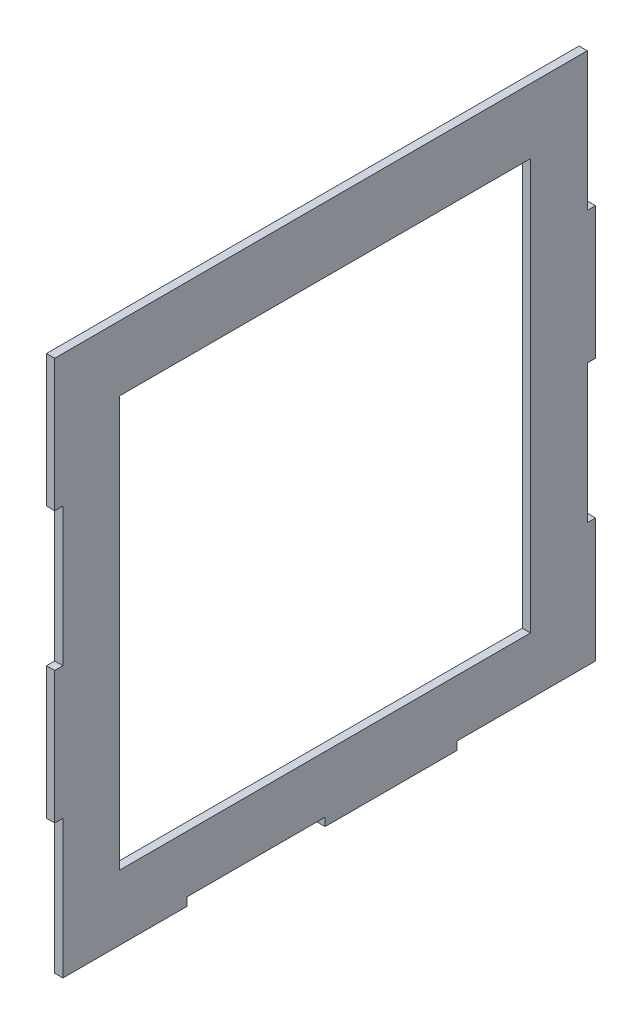
SolidWorks part; units mm, degrees
ref_plane "Front Plane" through (0, 0, 0) normal (0, 0, 1) x (1, 0, 0)
ref_plane "Top Plane" through (0, 0, 0) normal (0, 1, 0) x (1, 0, 0)
ref_plane "Right Plane" through (0, 0, 0) normal (1, 0, 0) x (0, 0, -1)
sketch "Sketch2" plane through (0, 0, 0) normal (1, 0, 0) x (0, 0, -1)
  line L1 (-197.5, -197.5) -> (197.5, -197.5)
  line L2 (-197.5, -197.5) -> (-197.5, 197.5)
  line L3 (-197.5, 197.5) -> (197.5, 197.5)
  line L4 (197.5, -197.5) -> (197.5, 197.5)
  line L5 (-197.5, -197.5) -> (197.5, 197.5) construction
  line L6 (-197.5, 197.5) -> (197.5, -197.5) construction
  line L7 (-150, -150) -> (150, -150)
  line L8 (-150, -150) -> (-150, 150)
  line L9 (-150, 150) -> (150, 150)
  line L10 (150, -150) -> (150, 150)
  line L11 (-150, -150) -> (150, 150) construction
  line L12 (-150, 150) -> (150, -150) construction
  line L13 (197.5, -197.5) -> (96.5, -197.5)
  line L14 (197.5, -197.5) -> (197.5, -191.5)
  line L15 (197.5, -191.5) -> (96.5, -191.5)
  line L16 (96.5, -197.5) -> (96.5, -191.5)
  line L17 (0, -197.5) -> (-101, -197.5)
  line L18 (0, -197.5) -> (0, -191.5)
  line L19 (0, -191.5) -> (-101, -191.5)
  line L20 (-101, -197.5) -> (-101, -191.5)
  line L21 (-197.5, -197.5) -> (-191.5, -197.5)
  line L22 (-197.5, -197.5) -> (-197.5, -96.5)
  line L23 (-197.5, -96.5) -> (-191.5, -96.5)
  line L24 (-191.5, -197.5) -> (-191.5, -96.5)
  line L25 (-197.5, 0) -> (-191.5, 0)
  line L26 (-197.5, 0) -> (-197.5, 101)
  line L27 (-197.5, 101) -> (-191.5, 101)
  line L28 (-191.5, 0) -> (-191.5, 101)
  line L29 (197.5, 197.5) -> (191.5, 197.5)
  line L30 (197.5, 197.5) -> (197.5, 96.5)
  line L31 (197.5, 96.5) -> (191.5, 96.5)
  line L32 (191.5, 197.5) -> (191.5, 96.5)
  line L33 (197.5, 0) -> (191.5, 0)
  line L34 (197.5, 0) -> (197.5, -101)
  line L35 (197.5, -101) -> (191.5, -101)
  line L36 (191.5, 0) -> (191.5, -101)
  point P0 (0, 0)
  point P6 (0, 0)
  dimension "D1" = 395
  dimension "D2" = 300
  dimension "D3" = 101
  dimension "D4" = 6
extrude "Boss-Extrude2" add sketch "Sketch2" along normal blind 6 contours L36 L33 L4 L31 L32 L3 L2 L27 L28 L25 L23 L24 L1 L20 L19 L18 L16 L15 L35 L10 L7 L8 L9
